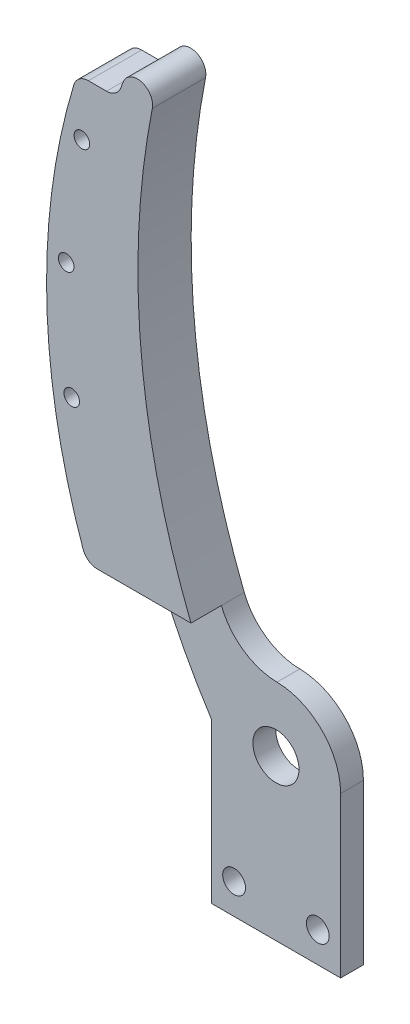
SolidWorks part; units mm, degrees
ref_plane "前视基准面" through (0, 0, 0) normal (0, 0, 1) x (1, 0, 0)
ref_plane "上视基准面" through (0, 0, 0) normal (0, 1, 0) x (1, 0, 0)
ref_plane "右视基准面" through (0, 0, 0) normal (1, 0, 0) x (0, 0, -1)
sketch "草图1" plane through (0, 0, 0) normal (0, 0, 1) x (1, 0, 0)
  line L0 (0, 0) -> (17, 0)
  line L1 (17, 0) -> (17, 21)
  line L2 (17, 21) -> (0, 21) construction
  line L3 (0, 21) -> (0, 0)
  circle A0 centre (8.5, 21) radius 3.5
  arc A1 (17, 21) -> (8.6391, 29.4989) centre (8.5, 21) ccw
  arc A2 (8.6391, 29.4989) -> (1.3276, 34.5634) centre (8.77, 37.4978) cw
  arc A3 (1.3276, 34.5634) -> (-3.7485, 90.6126) centre (94.3577, 71.2432) cw
  arc A4 (-3.7485, 90.6126) -> (-7.5824, 91.7046) centre (-5.7106, 91) ccw
  arc A5 (-7.5824, 91.7046) -> (0, 21) centre (66.3533, 63.8746) ccw
  circle A7 centre (94.3577, 71.2432) radius 100 construction
  dimension "D3" = 7
  dimension "D4" = 17
  dimension "D5" = 70
  dimension "D6" = 100
  dimension "D7" = 79
  dimension "D8" = 2
  dimension "D9" = 8
  dimension "D2" = 21
  dimension "D11" = 85.8577
  dimension "D12" = 50.2432
extrude "凸台-拉伸1" add sketch "草图1" along normal blind 3
sketch "草图2" plane through (0, 0, 0) normal (0, 0, -1) x (-1, 0, 0)
  line L0 (-8.5, 0) -> (-8.5, 11.5766) construction
  line L1 (0, 0) -> (-17, 0) construction
  line L2 (-17, 0) -> (-17, 21) construction
  circle A0 centre (-14, 4) radius 1.5
  circle A1 centre (-3, 4) radius 1.5
  dimension "D3" = 3
  dimension "D1" = 4
  dimension "D2" = 3
extrude "切除-拉伸1" cut sketch "草图2" against normal blind 10
sketch "草图3" plane through (0, 0, 3) normal (0, 0, 1) x (1, 0, 0)
  line L0 (-7.0078, 34.5634) -> (1.3276, 34.5634)
  line L3 (0, 21) -> (0, 0)
  line L4 (0, 0) -> (17, 0)
  line L5 (17, 0) -> (17, 21)
  line L6 (0, 21) -> (0, 0)
  line L7 (0, 0) -> (17, 0)
  line L8 (17, 0) -> (17, 21)
  arc A5 (17, 21) -> (8.6391, 29.4989) centre (8.5, 21) ccw
  arc A6 (1.3276, 34.5634) -> (8.6391, 29.4989) centre (8.77, 37.4978) ccw
  arc A7 (-3.7485, 90.6126) -> (1.3276, 34.5634) centre (94.3577, 71.2432) ccw
  arc A8 (-3.7485, 90.6126) -> (-7.5824, 91.7046) centre (-5.7106, 91) ccw
  arc A9 (-7.5824, 91.7046) -> (0, 21) centre (66.3533, 63.8746) ccw
  arc A10 (17, 21) -> (8.6391, 29.4989) centre (8.5, 21) ccw
  arc A11 (1.3276, 34.5634) -> (8.6391, 29.4989) centre (8.77, 37.4978) ccw
  arc A12 (-3.7485, 90.6126) -> (1.3276, 34.5634) centre (94.3577, 71.2432) ccw
  arc A13 (-3.7485, 90.6126) -> (-7.5824, 91.7046) centre (-5.7106, 91) ccw
  arc A14 (-7.5824, 91.7046) -> (0, 21) centre (66.3533, 63.8746) ccw
  arc M17 (1.3276, 34.5634) -> (-3.7485, 90.6126) centre (94.3577, 71.2432) cw
  arc M18 (-3.7485, 90.6126) -> (-7.5824, 91.7046) centre (-5.7106, 91) ccw
  arc M19 (-7.5824, 91.7046) -> (0, 21) centre (66.3533, 63.8746) ccw
  dimension "D1" = 0
extrude "凸台-拉伸2" add sketch "草图3" along normal blind 4 contours L0 M19 M17 M18
sketch "草图8" plane through (0, 0, 0) normal (0, 0, -1) x (-1, 0, 0)
  line L0 (8.3533, 89.5634) -> (13.6222, 89.5634)
  line L2 (8.3533, 89.5634) -> (17.2136, 89.5634) construction
  line L3 (15.059, 84.5634) -> (17.2136, 84.5634) construction
  line L4 (7.0078, 34.5634) -> (-1.3276, 34.5634) construction
  line L5 (12.3667, 34.5634) -> (7.0078, 34.5634)
  arc A0 (0, 21) -> (7.5824, 91.7046) centre (-66.3533, 63.8746) ccw construction
  arc A1 (7.0078, 34.5634) -> (8.3533, 89.5634) centre (-66.3533, 63.8746) ccw
  arc A2 (12.3667, 34.5634) -> (13.6222, 89.5634) centre (-66.3533, 63.8746) ccw
  arc A3 (4.1996, 18.2864) -> (15.059, 84.5634) centre (-66.3533, 63.8746) ccw construction
  arc A4 (0, 21) -> (8.3533, 89.5634) centre (-66.3533, 63.8746) ccw construction
  dimension "D2" = 55
  dimension "D1" = 5
extrude "凸台-拉伸5" add sketch "草图8" against normal up to surface (7 mm away) up to face at (-6.4701, 63.1977, 7)
fillet "圆角1" radius 2 4 edges at (-12.3667, 34.5634, 3.5) (-13.6222, 89.5634, 3.5) (-8.3533, 89.5634, 3.5) (-7.0078, 34.5634, 1.5)
sketch "草图10" plane through (0, 0, 0) normal (0, 0, -1) x (-1, 0, 0)
  circle A1 centre (13.0089, 82.419) radius 1.173
  arc A2 (10.4934, 36.7299) -> (11.6718, 87.419) centre (-66.3533, 63.8746) ccw
  arc A3 (10.4934, 36.7299) -> (11.6718, 87.419) centre (-66.3533, 63.8746) ccw
  circle A4 centre (15.0696, 67.419) radius 1.5898
  circle A5 centre (14.3375, 52.419) radius 1.4538
  point P9 (-20.3597, 65.6893)
  point P10 (13.0089, 82.419)
  point P11 (15.0696, 67.419)
  point P12 (14.3375, 52.419)
  dimension "D2" = 5
  dimension "D3" = 15
  dimension "D4" = 15
  dimension "D1" = 2.5
hole_wizard "M2.5 螺纹孔1" positions "草图10" profile "草图11" tap size "M2.5" standard "GB" end condition through all
sketch "草图11" plane through (-14.3375, 52.419, 0) normal (1, 0, 0) x (0, 1, 0)
  line L0 (0, 0) -> (0, 7)
  line L1 (0, 7) -> (1.025, 7)
  line L2 (1.025, 7) -> (1.025, 0)
  line L5 (1.025, 0) -> (0, 0)
  line L11 (0, -6.35) -> (0, 107.95) construction
  dimension "通孔螺纹孔钻头直径" = 2.05
  dimension "通孔螺纹孔钻头深度" = 7
sketch "草图12" plane through (0, 0, 0) normal (0, 0, -1) x (-1, 0, 0)
  circle A0 centre (-8.5, 21) radius 4.9536
  circle A1 centre (-8.5, 21) radius 3.03
  dimension "D1" = 6.06
extrude "凸台-拉伸6" add sketch "草图12" against normal up to surface (3 mm away) up to face at (3.7493, 21.8374, 3)
